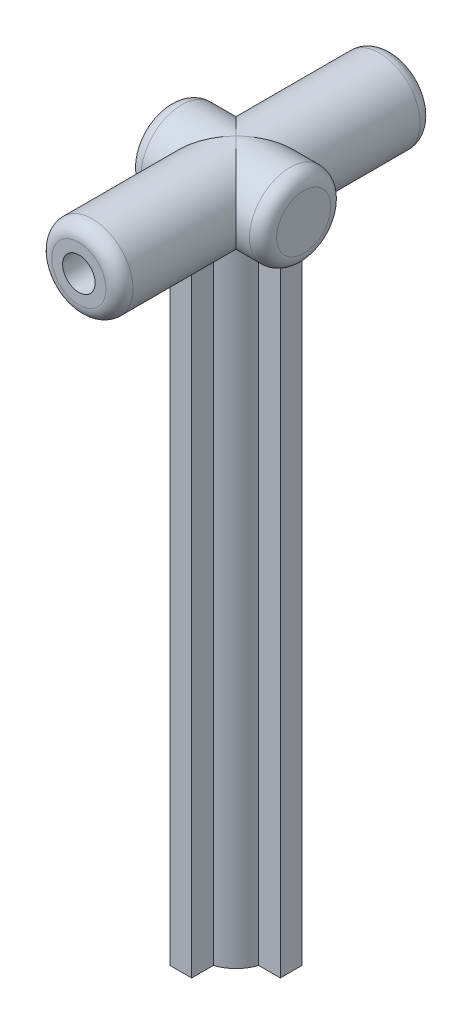
SolidWorks part; units mm, degrees
material "PVC Rigid"
ref_plane "Front Plane" through (0, 0, 0) normal (0, 0, 1) x (1, 0, 0)
ref_plane "Top Plane" through (0, 0, 0) normal (0, 1, 0) x (1, 0, 0)
ref_plane "Right Plane" through (0, 0, 0) normal (1, 0, 0) x (0, 0, -1)
sketch "Sketch3" plane through (0, 0, 0) normal (0, 1, 0) x (1, 0, 0)
  line L4 (-1.016, 3.1418) -> (-1.016, 5.1738)
  line L5 (1.016, 3.1418) -> (1.016, 5.1738)
  line L6 (1.016, 5.1738) -> (-1.016, 5.1738)
  line L7 (3.1418, 1.016) -> (5.1738, 1.016)
  line L8 (3.1418, -1.016) -> (5.1738, -1.016)
  line L9 (5.1738, -1.016) -> (5.1738, 1.016)
  line L10 (1.016, -3.1418) -> (1.016, -5.1738)
  line L11 (1.016, -5.1738) -> (-1.016, -5.1738)
  line L12 (-1.016, -3.1418) -> (-1.016, -5.1738)
  line L13 (-3.1418, -1.016) -> (-5.1738, -1.016)
  line L14 (-5.1738, -1.016) -> (-5.1738, 1.016)
  line L15 (-3.1418, 1.016) -> (-5.1738, 1.016)
  arc A8 (-1.016, 3.1418) -> (-3.1418, 1.016) centre (0, 0) ccw
  arc A9 (1.016, 3.1418) -> (3.1418, 1.016) centre (0, 0) cw
  arc A10 (3.1418, -1.016) -> (1.016, -3.1418) centre (0, 0) cw
  arc A11 (-1.016, -3.1418) -> (-3.1418, -1.016) centre (0, 0) cw
  circle A12 centre (0, 0) radius 5.2726 construction
  dimension "D1" = 3.302
  dimension "D2" = 2.032
extrude "Boss-Extrude2" add sketch "Sketch3" along normal blind 58.42
sketch "Sketch4" plane through (0, 58.42, 0) normal (0, 1, 0) x (1, 0, 0)
  circle A0 centre (0, 0) radius 1.905
  dimension "D1" = 3.81
extrude "Cut-Extrude1" cut sketch "Sketch4" against normal through all
ref_plane "Plane1" through (0, 0, 0) normal (0, 0, 1) x (1, 0, 0)
sketch "Sketch5" plane through (0, 0, 0) normal (0, 0, 1) x (1, 0, 0)
  line L0 (3.1418, 58.42) -> (1.016, 58.42) construction
  circle A0 centre (0, 61.468) radius 3.81
  dimension "D1" = 3.048
  dimension "D2" = 7.62
extrude "Boss-Extrude3" add sketch "Sketch5" along normal blind 14.732 and the other way blind 14.732 separate body
sketch "Sketch6" plane through (0, 0, 14.732) normal (0, 0, 1) x (1, 0, 0)
  circle A0 centre (0, 61.468) radius 3.7382
mirror "Mirror1" about plane through (0, 0, 0) normal (0, 0, 1) of bodies 104 105
extrude "Cut-Extrude3" cut sketch "Sketch6" against normal blind 12.7
mirror "Mirror2" about plane through (0, 0, 0) normal (0, 0, 1) of bodies 107
ref_plane "Plane2" through (0, 0, 0) normal (1, 0, 0) x (0, 0, -1)
sketch "Sketch7" plane through (0, 0, 0) normal (1, 0, 0) x (0, 0, -1)
  line L0 (0, 8.382) -> (0, -8.382) construction
  line L1 (-1.016, 58.42) -> (-3.1418, 58.42) construction
  circle A0 centre (0, 61.468) radius 3.81
  dimension "D1" = 7.62
  dimension ".12" = 3.048
extrude "Boss-Extrude4" add sketch "Sketch7" along normal blind 6.35 and the other way blind 6.35
ref_plane "Plane3" through (0, 0, 0) normal (0, 0, 1) x (1, 0, 0)
fillet "Fillet2" radius 1.27 1 edges at (3.81, 61.468, -14.732)
fillet "Fillet3" radius 1.27 2 edges at (-6.35, 61.468, -3.81) (6.35, 61.468, -3.81)
fillet "Fillet4" radius 1.27 1 edges at (3.81, 61.468, 14.732)
sketch "Sketch8" plane through (0, 0, 14.732) normal (0, 0, 1) x (1, 0, 0)
  line L0 (-0.635, 57.7113) -> (0.635, 57.7113)
  line L1 (-0.635, 57.7113) -> (-0.635, 57.3696)
  line L2 (-0.635, 57.3696) -> (0.635, 57.3696)
  line L3 (0.635, 57.3696) -> (0.635, 57.7113)
  circle A0 centre (0, 61.468) radius 1.524
  arc A1 (0, 65.278) -> (0, 57.658) centre (0, 61.468) ccw construction
  arc A2 (0, 65.278) -> (0, 57.658) centre (0, 61.468) ccw construction
  arc A3 (0, 57.658) -> (0, 65.278) centre (0, 61.468) ccw construction
  dimension "D1" = 2.286
  dimension "D2" = 1.27
  dimension "D3" = 0.3417
extrude "Cut-Extrude4" cut sketch "Sketch8" against normal blind 7.62
mirror "Mirror3" about plane through (0, 0, 0) normal (0, 0, 1) of "Cut-Extrude4"
